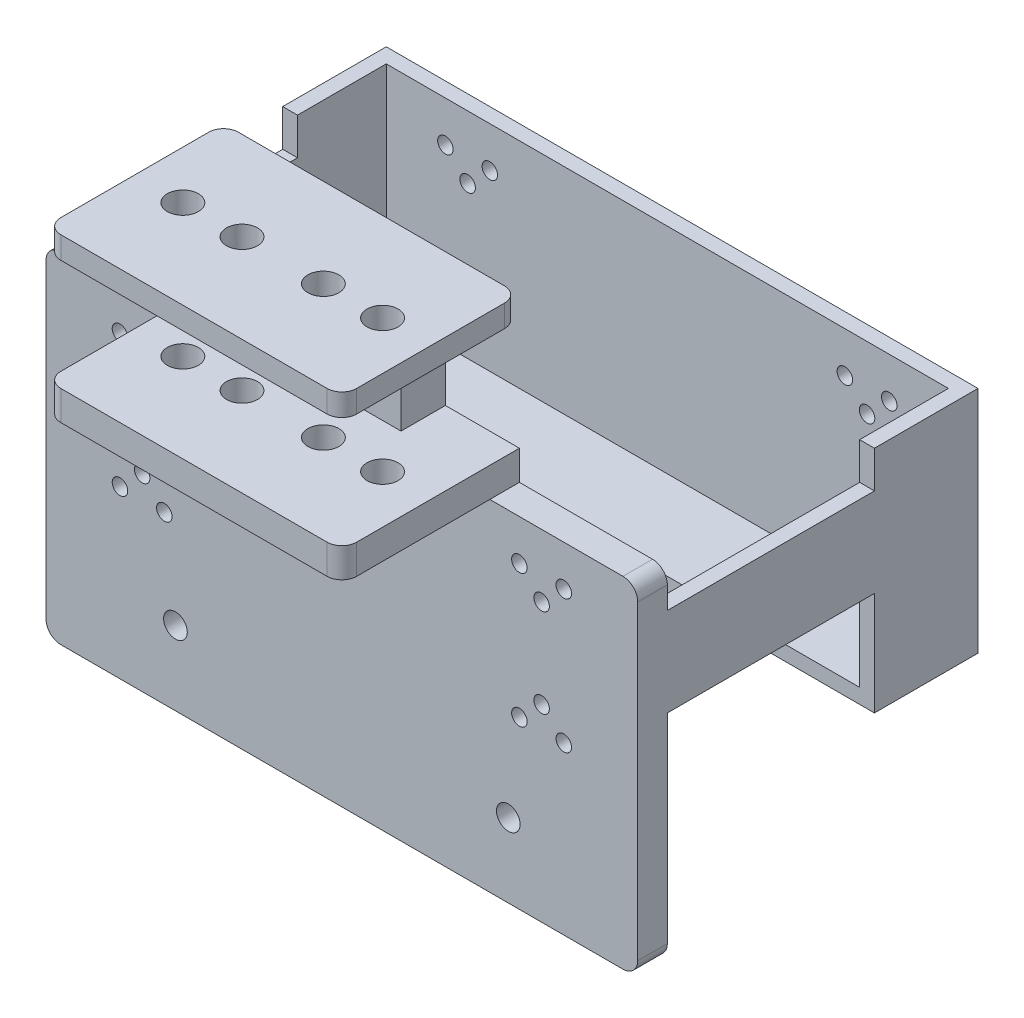
SolidWorks part; units mm, degrees
ref_plane "前视基准面" through (0, 0, 0) normal (0, 0, 1) x (1, 0, 0)
ref_plane "上视基准面" through (0, 0, 0) normal (0, 1, 0) x (1, 0, 0)
ref_plane "右视基准面" through (0, 0, 0) normal (1, 0, 0) x (0, 0, -1)
other "Configuration Table"
sketch "草图1" plane through (0, 0, 0) normal (0, 0, 1) x (1, 0, 0)
  line L1 (-40, 14.5) -> (40, 14.5)
  line L2 (-40, 14.5) -> (-40, -14.5)
  line L3 (-40, -14.5) -> (40, -14.5)
  line L4 (40, 14.5) -> (40, -14.5)
  line L5 (-40, 14.5) -> (40, -14.5) construction
  line L6 (-40, -14.5) -> (40, 14.5) construction
  point P0 (0, 0)
extrude "凸台-拉伸1" add sketch "草图1" along normal blind 2
sketch "草图4" plane through (0, 0, 2) normal (0, 0, 1) x (1, 0, 0)
  line L0 (40, -14.5) -> (40, 14.5) construction
  line L1 (40, 14.5) -> (38, 14.5)
  line L2 (40, 14.5) -> (40, -14.5)
  line L3 (40, -14.5) -> (38, -14.5)
  line L4 (38, 14.5) -> (38, -14.5)
  line L5 (40, 14.5) -> (-40, 14.5) construction
  line L6 (-40, -14.5) -> (40, -14.5) construction
  line L8 (-40, 14.5) -> (-38, 14.5)
  line L9 (-40, 14.5) -> (-40, -14.5)
  line L10 (-40, -14.5) -> (-38, -14.5)
  line L11 (-38, 14.5) -> (-38, -14.5)
  dimension "D1" = 2
  dimension "D2" = 2
extrude "凸台-拉伸2" add sketch "草图4" along normal blind 12
sketch "草图6" plane through (0, -14.5, 0) normal (0, -1, 0) x (1, 0, 0)
  line L1 (-40, 0) -> (40, 0)
  line L2 (-40, 0) -> (-40, 14)
  line L3 (-40, 14) -> (40, 14)
  line L4 (40, 0) -> (40, 14)
extrude "凸台-拉伸4" add sketch "草图6" along normal blind 2
sketch "草图7" plane through (0, 0, 14) normal (0, 0, 1) x (1, 0, 0)
  line L0 (-40, 14.5) -> (-40, -16.5) construction
  line L1 (-40, 9.5) -> (-38, 9.5)
  line L2 (-40, 9.5) -> (-40, -2.5)
  line L3 (-40, -2.5) -> (-38, -2.5)
  line L4 (-38, 9.5) -> (-38, -2.5)
  line L5 (-38, -14.5) -> (-38, 14.5) construction
  line L6 (-38, 14.5) -> (-40, 14.5) construction
  line L7 (38, 14.5) -> (38, -14.5) construction
  line L8 (38, 9.5) -> (40, 9.5)
  line L9 (38, 9.5) -> (38, -2.5)
  line L10 (38, -2.5) -> (40, -2.5)
  line L11 (40, 9.5) -> (40, -2.5)
  line L12 (40, -16.5) -> (40, 14.5) construction
  dimension "D1" = 5
  dimension "D2" = 12
extrude "凸台-拉伸5" add sketch "草图7" along normal blind 28
sketch "草图8" plane through (0, 0, 42) normal (0, 0, 1) x (1, 0, 0)
  line L1 (-40, 14.5) -> (40, 14.5)
  line L2 (-40, 14.5) -> (-40, -16.5)
  line L3 (-40, -16.5) -> (40, -16.5)
  line L4 (40, 14.5) -> (40, -16.5)
extrude "凸台-拉伸6" add sketch "草图8" along normal blind 4
sketch "草图2" plane through (0, 0, 2) normal (0, 0, 1) x (1, 0, 0)
  line L0 (0, 0) -> (27, 0) construction
  line L2 (0, 0) -> (0, 13.1686) construction
  circle A0 centre (-30, 9) radius 1.05
  circle A2 centre (-24, 9) radius 1.05
  circle A3 centre (-27, 6) radius 1.05
  circle A4 centre (-27, -6) radius 1.05
  circle A5 centre (-24, -9) radius 1.05
  circle A7 centre (-30, -9) radius 1.05
  circle A8 centre (27, -6) radius 1.05
  circle A9 centre (30, -9) radius 1.05
  circle A10 centre (24, -9) radius 1.05
  circle A12 centre (27, 6) radius 1.05
  circle A13 centre (30, 9) radius 1.05
  circle A14 centre (24, 9) radius 1.05
  point P3 (27, 6)
  point P5 (27, 9)
  point P6 (30, 9)
  point P7 (24, 9)
  point P8 (24, -9)
  point P9 (27, -6)
  point P10 (27, -9)
  point P11 (30, -9)
  point P14 (-30, -9)
  point P15 (-27, -9)
  point P16 (-27, -6)
  point P17 (-24, -9)
  point P18 (-24, 9)
  point P19 (-30, 9)
  point P20 (-27, 9)
  point P21 (-27, 6)
  dimension "D2" = 27
  dimension "D3" = 6
  dimension "D4" = 3
  dimension "D5" = 3
  dimension "D6" = 3
extrude "切除-拉伸1" cut sketch "草图2" against normal through all and the other way up to surface other way up to face at (0, -1, 46)
sketch "草图12" plane through (0, 14.5, 0) normal (0, 1, 0) x (1, 0, 0)
  line L0 (40, -42) -> (-40, -42) construction
  line L1 (-20, -42) -> (20, -42)
  line L2 (-20, -42) -> (-20, -66)
  line L3 (-20, -66) -> (20, -66)
  line L4 (20, -42) -> (20, -66)
  dimension "D1" = 24
  dimension "D2" = 20
  dimension "D3" = 20
extrude "凸台-拉伸9" add sketch "草图12" along normal blind 4
sketch "草图13" plane through (0, 18.5, 0) normal (0, 1, 0) x (1, 0, 0)
  line L0 (-20, -54) -> (20, -54) construction
  line L1 (-20, -42) -> (-20, -66) construction
  line L2 (20, -66) -> (20, -42) construction
  circle A0 centre (-13.5, -54) radius 2.1
  circle A1 centre (-5.5, -54) radius 2.1
  circle A2 centre (5.5, -54) radius 2.1
  circle A3 centre (13.5, -54) radius 2.1
  point P6 (-5.5, -54)
  point P7 (-13.5, -54)
  point P8 (5.5, -54)
  point P9 (13.5, -54)
  point P10 (0, -54)
  dimension "D1" = 5.5
  dimension "D2" = 5.5
  dimension "D3" = 8
  dimension "D4" = 8
extrude "切除-拉伸3" cut sketch "草图13" against normal up to next and the other way through all
sketch "草图14" plane through (0, 18.5, 0) normal (0, 1, 0) x (1, 0, 0)
  line L0 (-20, -45) -> (20, -45) construction
  line L1 (-20, -42) -> (-20, -66) construction
  line L2 (20, -66) -> (20, -42) construction
  line L3 (20, -42) -> (-20, -42) construction
  line L4 (-9.9962, -48) -> (9.9962, -48)
  line L5 (-9.9962, -48) -> (-9.9962, -42)
  line L6 (-9.9962, -42) -> (9.9962, -42)
  line L7 (9.9962, -48) -> (9.9962, -42)
  line L8 (-9.9962, -48) -> (9.9962, -42) construction
  line L9 (-9.9962, -42) -> (9.9962, -48) construction
  point P0 (-5.5, -54)
  point P8 (0, -45)
  dimension "D1" = 9
extrude "凸台-拉伸10" add sketch "草图14" along normal blind 15
sketch "草图15" plane through (0, 33.5, 0) normal (0, 1, 0) x (1, 0, 0)
  line L0 (9.9962, -42) -> (-9.9962, -42) construction
  line L1 (-20, -42) -> (20, -42)
  line L2 (-20, -42) -> (-20, -66)
  line L3 (-20, -66) -> (20, -66)
  line L4 (20, -42) -> (20, -66)
  point P7 (0, -42)
  point P8 (0, -42)
  dimension "D1" = 40
extrude "凸台-拉伸11" add sketch "草图15" along normal blind 3
sketch "草图16" plane through (0, 36.5, 0) normal (0, 1, 0) x (1, 0, 0)
  line L0 (-20, -54) -> (20, -54) construction
  line L1 (-20, -42) -> (-20, -66) construction
  line L2 (20, -66) -> (20, -42) construction
  circle A0 centre (-13.5, -54) radius 2.1
  circle A1 centre (-5.5, -54) radius 2.1
  circle A2 centre (5.5, -54) radius 2.1
  circle A3 centre (13.5, -54) radius 2.1
  point P6 (-5.5, -54)
  point P7 (-13.5, -54)
  point P8 (5.5, -54)
  point P9 (13.5, -54)
  point P11 (0, -54)
  dimension "D1" = 8
  dimension "D2" = 5.5
  dimension "D3" = 5.5
  dimension "D4" = 8
extrude "切除-拉伸4" cut sketch "草图16" against normal blind 3
sketch "草图21" plane through (0, 0, 46) normal (0, 0, 1) x (1, 0, 0)
  line L0 (0, -16.5) -> (0, 0) construction
  line L1 (-40, 14.5) -> (-40, -16.5) construction
  line L2 (0, -16.5) -> (40, -16.5)
  line L3 (-40, -16.5) -> (40, -16.5) construction
  line L4 (40, -16.5) -> (40, -31.5)
  line L5 (40, -31.5) -> (-40, -31.5)
  line L6 (-40, -31.5) -> (-40, -16.5)
  line L7 (-40, -16.5) -> (0, -16.5)
  line L8 (40, -16.5) -> (40, 14.5) construction
  point P4 (16.1414, -16.5)
  dimension "D3" = 15
extrude "凸台-拉伸14" add sketch "草图21" against normal up to surface (4 mm away) up to face at (31.05, -9, 42)
sketch "草图22" plane through (0, 0, 46) normal (0, 0, 1) x (1, 0, 0)
  line L0 (-40, -21.5) -> (40, -21.5) construction
  line L4 (-40, -31.5) -> (40, -31.5) construction
  circle A0 centre (-22.5, -21.5) radius 1.6
  circle A1 centre (22.5, -21.5) radius 1.6
  point P6 (22.5, -21.5)
  point P7 (-22.5, -21.5)
  point P8 (0, -21.5)
  point P13 (0, 0)
  point P14 (0, 0)
  dimension "D3" = 10
  dimension "D1" = 22.5
  dimension "D2" = 22.5
extrude "切除-拉伸5" cut sketch "草图22" against normal up to surface (4 mm away)
fillet "圆角1" radius 2 10 edges at (-20, 35, 42) (20, 35, 42) (20, 35, 66) (20, 16.5, 66) (-20, 35, 66) (-20, 16.5, 66) (40, 14.5, 44) (-40, 14.5, 44) (-40, -31.5, 44) (40, -31.5, 44)
